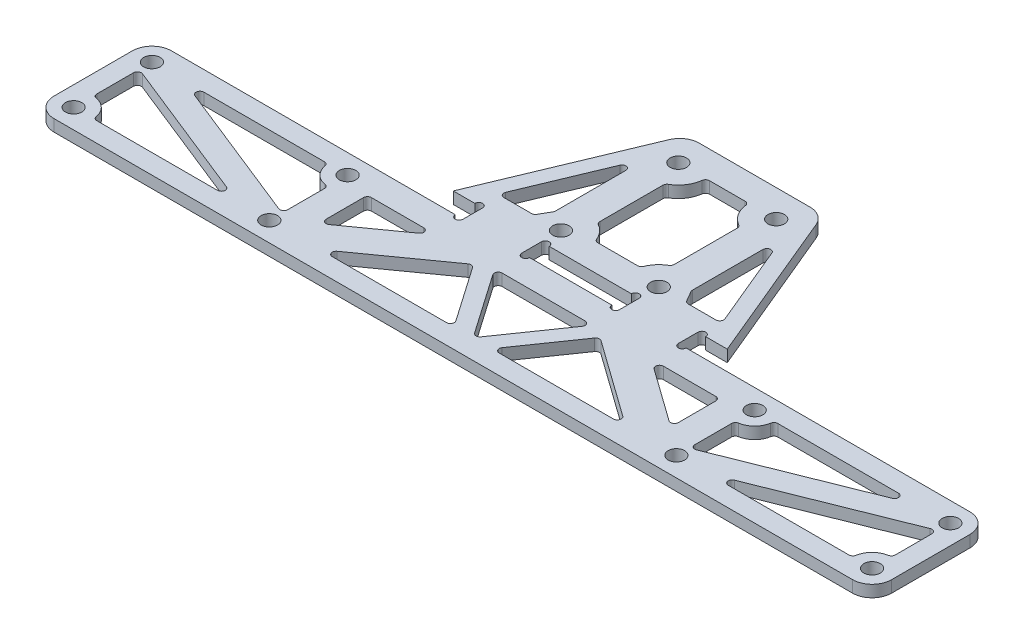
SolidWorks part; units mm, degrees
material "Thornel Mat VMA"
ref_plane "前视基准面" through (0, 0, 0) normal (0, 0, 1) x (1, 0, 0)
ref_plane "上视基准面" through (0, 0, 0) normal (0, 1, 0) x (1, 0, 0)
ref_plane "右视基准面" through (0, 0, 0) normal (1, 0, 0) x (0, 0, -1)
sketch "草图1" plane through (0, 0, 0) normal (0, 1, 0) x (1, 0, 0)
  line L1 (0, 0) -> (25, 0) construction
  line L2 (0, 0) -> (0, 30) construction
  line L3 (0, 30) -> (25, 30) construction
  line L5 (-5, 37) -> (30, 37)
  line L7 (-17, -10) -> (-94.5, -10)
  line L8 (-94.5, -10) -> (-94.5, -40)
  line L9 (-94.5, -40) -> (119.5, -40)
  line L10 (12.5, 37) -> (12.5, -40) construction
  line L11 (119.5, -10) -> (119.5, -40)
  line L12 (42, -10) -> (119.5, -10)
  line L13 (64.5, -15) -> (64.5, -35) construction
  line L14 (-89.5, -15) -> (-39.5, -15) construction
  line L15 (-89.5, -15) -> (-89.5, -35) construction
  line L16 (-89.5, -35) -> (-39.5, -35) construction
  line L17 (-39.5, -15) -> (-39.5, -35) construction
  line L18 (114.5, -35) -> (64.5, -35) construction
  line L19 (114.5, -15) -> (114.5, -35) construction
  line L20 (114.5, -15) -> (64.5, -15) construction
  line L21 (25, 0) -> (25, 30) construction
  line L22 (2, -10) -> (23, -10)
  line L23 (0, -10) -> (0, -5)
  line L24 (2, -5) -> (23, -5)
  line L25 (25, -10) -> (25, -5)
  line L26 (-15, -10) -> (-15, -5)
  line L27 (-17, -5) -> (-22.5, -5)
  line L28 (-22.5, -5) -> (-5, 37)
  line L29 (40, -10) -> (40, -5)
  line L30 (42, -5) -> (47.5, -5)
  line L31 (47.5, -5) -> (30, 37)
  circle A0 centre (0, 30) radius 2.1
  circle A2 centre (0, 0) radius 2.1
  circle A4 centre (-89.5, -15) radius 2.1
  circle A5 centre (-39.5, -15) radius 2.1
  circle A6 centre (-89.5, -35) radius 2.1
  circle A7 centre (-39.5, -35) radius 2.1
  circle A8 centre (64.5, -35) radius 2.1
  circle A9 centre (114.5, -35) radius 2.1
  circle A10 centre (64.5, -15) radius 2.1
  circle A11 centre (114.5, -15) radius 2.1
  circle A12 centre (25, 0) radius 2.1
  circle A13 centre (25, 30) radius 2.1
  arc A14 (0, -5) -> (2, -5) centre (1, -5) cw
  arc A15 (0, -10) -> (2, -10) centre (1, -10) ccw
  arc A16 (25, -10) -> (23, -10) centre (24, -10) cw
  arc A17 (25, -5) -> (23, -5) centre (24, -5) ccw
  arc A18 (-15, -10) -> (-17, -10) centre (-16, -10) cw
  arc A19 (-15, -5) -> (-17, -5) centre (-16, -5) ccw
  arc A20 (40, -10) -> (42, -10) centre (41, -10) ccw
  arc A21 (40, -5) -> (42, -5) centre (41, -5) cw
  dimension "D3" = 4.2
  dimension "D10" = 4.2
  dimension "D6" = 35
  dimension "D7" = 1
  dimension "D18" = 1
  dimension "D1" = 30
  dimension "D2" = 25
  dimension "D4" = 7
  dimension "D5" = 10
  dimension "D8" = 30
  dimension "D9" = 214
  dimension "D11" = 5
  dimension "D12" = 5
  dimension "D13" = 5
  dimension "D14" = 50
  dimension "D15" = 25
  dimension "D16" = 5
  dimension "D17" = 55
  dimension "D19" = 70
extrude "凸台-拉伸1" add sketch "草图1" along normal blind 3
fillet "圆角1" radius 5 6 edges at (30, 1.5, -37) (-5, 1.5, -37) (119.5, 1.5, 40) (119.5, 1.5, 10) (-94.5, 1.5, 40) (-94.5, 1.5, 10)
sketch "草图2" plane through (0, 3, 0) normal (0, 1, 0) x (1, 0, 0)
  line L0 (-89.5, -29.0839) -> (-89.5, -19.7081)
  line L1 (-88.1286, -18.7797) -> (-52.3989, -33.0715)
  line L2 (-52.7703, -35) -> (-83.5839, -35)
  line L3 (-89.5, -40) -> (114.5, -40) construction
  line L4 (-94.5, -15) -> (-94.5, -35) construction
  line L5 (-89.5, -15) -> (-39.5, -35) construction
  line L9 (-45.4161, -15) -> (-76.2297, -15)
  line L10 (-76.6011, -16.9285) -> (-40.8714, -31.2203)
  line L11 (-39.5, -30.2919) -> (-39.5, -20.9161)
  line L12 (-17, -10) -> (-89.5, -10) construction
  line L13 (12.5, 37) -> (12.5, -40) construction
  line L14 (26.6667, 37) -> (-1.6667, 37) construction
  line L15 (114.5, -15) -> (64.5, -35) construction
  line L16 (64.5, -30.2919) -> (64.5, -20.9161)
  line L17 (101.6011, -16.9285) -> (65.8714, -31.2203)
  line L18 (70.4161, -15) -> (101.2297, -15)
  line L19 (77.7703, -35) -> (108.5839, -35)
  line L20 (113.1286, -18.7797) -> (77.3989, -33.0715)
  line L21 (114.5, -29.0839) -> (114.5, -19.7081)
  line L22 (-14.5833, 0) -> (-7.5056, 0)
  line L23 (-5, 3.6077) -> (-5, 21.6)
  line L24 (-6.9231, 21.9846) -> (-15.5064, 1.3846)
  line L25 (-6.2821, 33.9231) -> (-22.5, -5) construction
  line L26 (-5.134, 3.1077) -> (-6.6395, 0.5)
  line L27 (30, 3.6077) -> (30, 21.6)
  line L28 (39.5833, 0) -> (32.5056, 0)
  line L29 (31.9231, 21.9846) -> (40.5064, 1.3846)
  line L30 (3, 23.0718) -> (3, 6.9282)
  line L31 (22, 23.0718) -> (22, 6.9282)
  line L32 (7.9373, 30) -> (17.0627, 30)
  line L33 (7.4162, 2) -> (17.5838, 2)
  line L34 (30.134, 3.1077) -> (31.6395, 0.5)
  line L35 (1.9119, -16.9285) -> (23.0881, -16.9285)
  line L37 (11.6786, -33.7457) -> (1.0906, -18.4989)
  line L38 (13.3214, -33.7457) -> (23.9094, -18.4989)
  line L39 (-32.5, -17.9285) -> (-32.5, -27.4853)
  line L40 (-30.9188, -28.299) -> (-17.5392, -18.7422)
  line L41 (-18.1205, -16.9285) -> (-31.5, -16.9285)
  line L42 (-23.9972, -33.1863) -> (-4.4897, -19.2524)
  line L43 (-3.0871, -19.4957) -> (6.5892, -33.4296)
  line L44 (5.7678, -35) -> (-23.4159, -35)
  line L45 (-15, -5) -> (-15, -10) construction
  line L46 (28.0871, -19.4957) -> (18.4108, -33.4296)
  line L47 (48.9972, -33.1863) -> (29.4897, -19.2524)
  line L48 (19.2322, -35) -> (48.4159, -35)
  line L49 (55.9188, -28.299) -> (42.5392, -18.7422)
  line L50 (57.5, -17.9285) -> (57.5, -27.4853)
  line L51 (43.1205, -16.9285) -> (56.5, -16.9285)
  line L52 (23, -5) -> (2, -5) construction
  arc A0 (-88.6667, -30.0699) -> (-84.5699, -34.1667) centre (-89.5, -35) cw
  circle A1 centre (-89.5, -15) radius 2.1 construction
  circle A2 centre (-39.5, -35) radius 2.1 construction
  arc A3 (-88.6667, -30.0699) -> (-89.5, -29.0839) centre (-88.5, -29.0839) cw
  arc A4 (-84.5699, -34.1667) -> (-83.5839, -35) centre (-83.5839, -34) ccw
  arc A5 (-52.3989, -33.0715) -> (-52.7703, -35) centre (-52.7703, -34) cw
  arc A6 (-89.5, -19.7081) -> (-88.1286, -18.7797) centre (-88.5, -19.7081) cw
  arc A12 (-44.4301, -15.8333) -> (-45.4161, -15) centre (-45.4161, -16) ccw
  arc A13 (-40.3333, -19.9301) -> (-39.5, -20.9161) centre (-40.5, -20.9161) cw
  arc A14 (-44.4301, -15.8333) -> (-40.3333, -19.9301) centre (-39.5, -15) ccw
  arc A15 (-40.8714, -31.2203) -> (-39.5, -30.2919) centre (-40.5, -30.2919) ccw
  arc A16 (-76.2297, -15) -> (-76.6011, -16.9285) centre (-76.2297, -16) ccw
  arc A17 (101.2297, -15) -> (101.6011, -16.9285) centre (101.2297, -16) cw
  arc A18 (65.8714, -31.2203) -> (64.5, -30.2919) centre (65.5, -30.2919) cw
  arc A19 (69.4301, -15.8333) -> (65.3333, -19.9301) centre (64.5, -15) cw
  arc A20 (65.3333, -19.9301) -> (64.5, -20.9161) centre (65.5, -20.9161) ccw
  arc A21 (69.4301, -15.8333) -> (70.4161, -15) centre (70.4161, -16) cw
  arc A22 (114.5, -19.7081) -> (113.1286, -18.7797) centre (113.5, -19.7081) ccw
  arc A23 (77.3989, -33.0715) -> (77.7703, -35) centre (77.7703, -34) ccw
  arc A24 (109.5699, -34.1667) -> (108.5839, -35) centre (108.5839, -34) cw
  arc A25 (113.6667, -30.0699) -> (114.5, -29.0839) centre (113.5, -29.0839) ccw
  arc A26 (113.6667, -30.0699) -> (109.5699, -34.1667) centre (114.5, -35) ccw
  circle A27 centre (0, 30) radius 2.1 construction
  arc A28 (-14.5833, 0) -> (-15.5064, 1.3846) centre (-14.5833, 1) cw
  arc A30 (-5, 21.6) -> (-6.9231, 21.9846) centre (-6, 21.6) ccw
  arc A32 (39.5833, 0) -> (40.5064, 1.3846) centre (39.5833, 1) ccw
  arc A33 (30, 21.6) -> (31.9231, 21.9846) centre (31, 21.6) cw
  arc A34 (3.5, 6.0622) -> (6.4892, 2.625) centre (0, 0) cw
  arc A35 (3.5, 23.9378) -> (6.9451, 29.125) centre (0, 30) ccw
  arc A36 (21.5, 6.0622) -> (18.5108, 2.625) centre (25, 0) ccw
  arc A37 (21.5, 23.9378) -> (18.0549, 29.125) centre (25, 30) cw
  arc A38 (18.0549, 29.125) -> (17.0627, 30) centre (17.0627, 29) ccw
  arc A39 (21.5, 23.9378) -> (22, 23.0718) centre (21, 23.0718) cw
  arc A40 (21.5, 6.0622) -> (22, 6.9282) centre (21, 6.9282) ccw
  arc A41 (18.5108, 2.625) -> (17.5838, 2) centre (17.5838, 3) cw
  arc A42 (6.4892, 2.625) -> (7.4162, 2) centre (7.4162, 3) ccw
  arc A43 (3, 6.9282) -> (3.5, 6.0622) centre (4, 6.9282) ccw
  arc A44 (3, 23.0718) -> (3.5, 23.9378) centre (4, 23.0718) cw
  arc A45 (6.9451, 29.125) -> (7.9373, 30) centre (7.9373, 29) cw
  arc A46 (31.6395, 0.5) -> (32.5056, 0) centre (32.5056, 1) ccw
  arc A47 (30, 3.6077) -> (30.134, 3.1077) centre (31, 3.6077) ccw
  arc A48 (-7.5056, 0) -> (-6.6395, 0.5) centre (-7.5056, 1) ccw
  arc A49 (-5, 3.6077) -> (-5.134, 3.1077) centre (-6, 3.6077) cw
  arc A50 (23.0881, -16.9285) -> (23.9094, -18.4989) centre (23.0881, -17.9285) cw
  arc A51 (13.3214, -33.7457) -> (11.6786, -33.7457) centre (12.5, -33.1753) cw
  arc A52 (1.9119, -16.9285) -> (1.0906, -18.4989) centre (1.9119, -17.9285) ccw
  arc A53 (6.5892, -33.4296) -> (5.7678, -35) centre (5.7678, -34) cw
  arc A54 (-4.4897, -19.2524) -> (-3.0871, -19.4957) centre (-3.9085, -20.0661) cw
  arc A55 (-23.9972, -33.1863) -> (-23.4159, -35) centre (-23.4159, -34) ccw
  arc A56 (-32.5, -27.4853) -> (-30.9188, -28.299) centre (-31.5, -27.4853) ccw
  arc A57 (-17.5392, -18.7422) -> (-18.1205, -16.9285) centre (-18.1205, -17.9285) ccw
  arc A58 (-32.5, -17.9285) -> (-31.5, -16.9285) centre (-31.5, -17.9285) cw
  arc A59 (29.4897, -19.2524) -> (28.0871, -19.4957) centre (28.9085, -20.0661) ccw
  arc A60 (18.4108, -33.4296) -> (19.2322, -35) centre (19.2322, -34) ccw
  arc A61 (48.9972, -33.1863) -> (48.4159, -35) centre (48.4159, -34) cw
  arc A62 (57.5, -27.4853) -> (55.9188, -28.299) centre (56.5, -27.4853) cw
  arc A63 (42.5392, -18.7422) -> (43.1205, -16.9285) centre (43.1205, -17.9285) cw
  arc A64 (57.5, -17.9285) -> (56.5, -16.9285) centre (56.5, -17.9285) ccw
  point P111 (31.9282, 0)
  point P114 (18, 30)
  point P117 (22, 23.6754)
  point P120 (22, 6.3246)
  point P123 (18.2918, 2)
  point P126 (6.7082, 2)
  point P129 (3, 6.3246)
  point P132 (3, 23.6754)
  point P135 (7, 30)
  point P138 (30, 3.3397)
  point P141 (-6.9282, 0)
  point P144 (-5, 3.3397)
  point P162 (25, -16.9285)
  point P165 (12.5, -34.9285)
  point P168 (0, -16.9285)
  point P177 (-32.5, -29.4285)
  point P180 (-15, -16.9285)
  point P183 (-32.5, -16.9285)
  dimension "D1" = 5
  dimension "D3" = 5
  dimension "D6" = 1
  dimension "D7" = 3
  dimension "D10" = 1
  dimension "D12" = 1
  dimension "D13" = 7
  dimension "D15" = 1
  dimension "D18" = 1
  dimension "D26" = 1
  dimension "D2" = 5
  dimension "D4" = 3
  dimension "D5" = 3
  dimension "D8" = 5
  dimension "D9" = 4
  dimension "D11" = 5
  dimension "D14" = 3
  dimension "D16" = 6
  dimension "D17" = 120
  dimension "D19" = 25
  dimension "D20" = 18
  dimension "D21" = 7
  dimension "D22" = 12.5
  dimension "D23" = 5
  dimension "D24" = 8
  dimension "D25" = 4
  dimension "D27" = 7
extrude "切除-拉伸1" cut sketch "草图2" against normal through all
